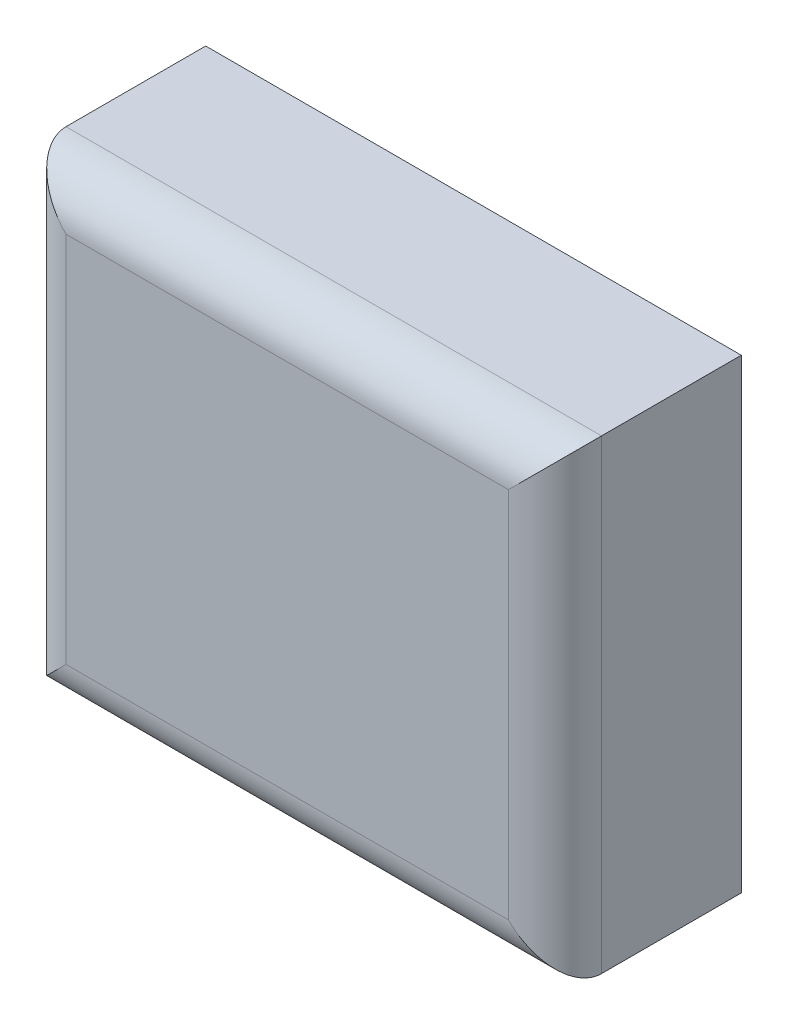
SolidWorks part; units mm, degrees
ref_plane "前视基准面" through (0, 0, 0) normal (0, 0, 1) x (1, 0, 0)
ref_plane "上视基准面" through (0, 0, 0) normal (0, 1, 0) x (1, 0, 0)
ref_plane "右视基准面" through (0, 0, 0) normal (1, 0, 0) x (0, 0, -1)
sketch "草图1" plane through (0, 0, 0) normal (0, 0, 1) x (1, 0, 0)
  line L0 (-14.5234, 0) -> (10.105, 0) construction
  line L1 (-5.75, 5) -> (5.75, 5)
  line L2 (-5.75, 5) -> (-5.75, -5)
  line L3 (-5.75, -5) -> (5.75, -5)
  line L4 (5.75, 5) -> (5.75, -5)
  line L5 (0, 6.5691) -> (0, -8.4702) construction
  dimension "D1" = 11.5
  dimension "D2" = 10
extrude "凸台-拉伸1" add sketch "草图1" along normal blind 4
fillet "圆角2" radius 1 4 edges at (0, 5, 4) (5.75, 0, 4) (-5.75, 0, 4) (0, -5, 4)
